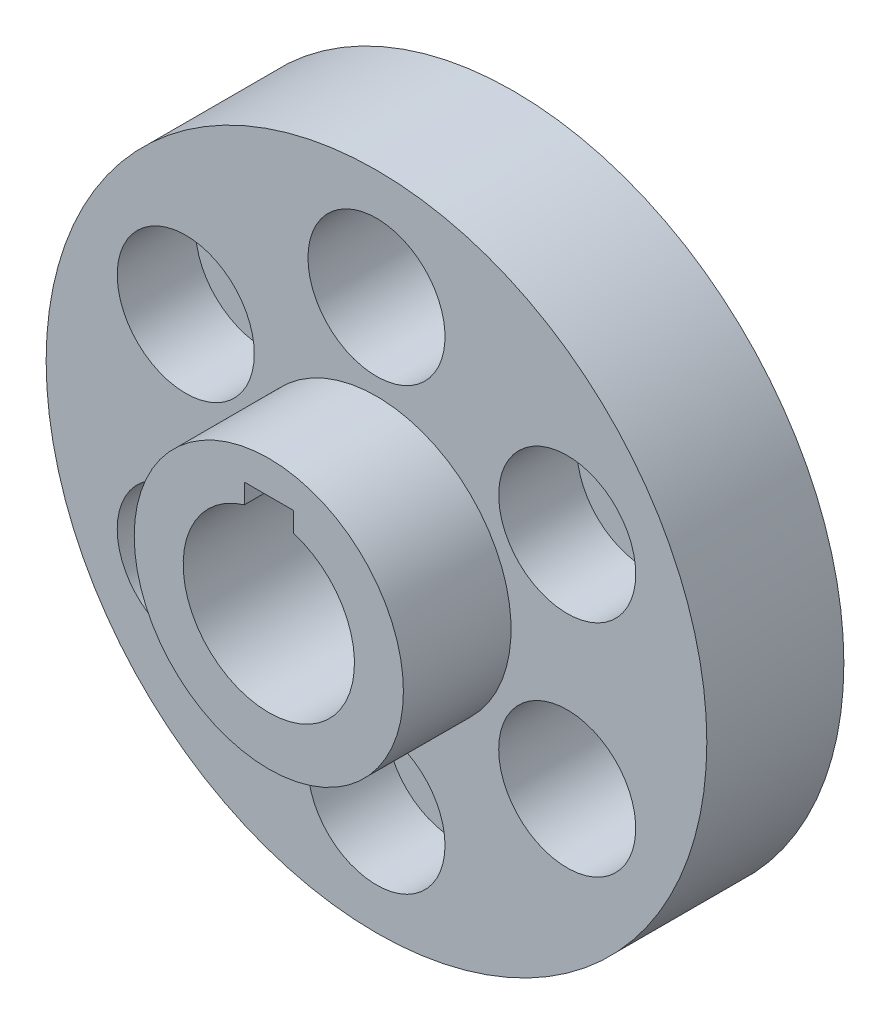
SolidWorks part; units mm, degrees
material "Cast Stainless Steel"
ref_plane "Front Plane" through (0, 0, 0) normal (0, 0, 1) x (1, 0, 0)
ref_plane "Top Plane" through (0, 0, 0) normal (0, 1, 0) x (1, 0, 0)
ref_plane "Right Plane" through (0, 0, 0) normal (1, 0, 0) x (0, 0, -1)
sketch "Sketch1" plane through (0, 0, 0) normal (0, 0, 1) x (1, 0, 0)
  line L0 (-5, 20.8) -> (5, 20.8)
  line L1 (0, 0) -> (50000, 0) construction
  line L2 (0, 3.0675) -> (0, 50003.0675) construction
  line L3 (5, 20.8) -> (5, 16.7705)
  line L4 (-5, 20.8) -> (-5, 16.7705)
  arc A0 (-5, 16.7705) -> (5, 16.7705) centre (0, 0) ccw
  circle A1 centre (0, 0) radius 27.5
  point P11 (0, 20.8)
  dimension "D1" = 35
  dimension "D2" = 55
  dimension "D3" = 20.8
  dimension "D4" = 10
extrude "Boss-Extrude1" add sketch "Sketch1" along normal blind 50
sketch "Sketch2" plane through (0, 0, 0) normal (0, 0, -1) x (-1, 0, 0)
  line L0 (0, 0) -> (-50000, 0) construction
  line L1 (0, 0) -> (0, 50000) construction
  circle A0 centre (0, 0) radius 67.5
  circle A1 centre (0, 45) radius 14
  circle A2 centre (38.9711, -22.5) radius 14
  circle A3 centre (-38.9711, -22.5) radius 14
  point P16 (0, 0)
  dimension "D1" = 135
  dimension "D2" = 28
  dimension "D3" = 45
extrude "Boss-Extrude2" add sketch "Sketch2" against normal blind 28
sketch "Sketch3" plane through (0, 0, 0) normal (0, 0, -1) x (-1, 0, 0)
  line L0 (0, 0) -> (-50000, 0) construction
  line L1 (0, 0) -> (0, 50000) construction
  circle A0 centre (0, -45) radius 9
  circle A2 centre (-38.9711, 22.5) radius 9
  circle A3 centre (38.9711, 22.5) radius 9
  point P13 (0, 0)
  dimension "D1" = 18
  dimension "D2" = 45
extrude "Cut-Extrude1" cut sketch "Sketch3" against normal blind 12 draft 7.5
sketch "Sketch4" plane through (0, 0, 28) normal (0, 0, 1) x (1, 0, 0)
  line L0 (0, 0) -> (0, -50000) construction
  line L1 (0, 0) -> (-50000, 0) construction
  circle A0 centre (0, -45) radius 14
  circle A1 centre (-38.9711, 22.5) radius 14
  circle A2 centre (38.9711, 22.5) radius 14
  point P13 (0, 0)
  dimension "D3" = 3
extrude "Cut-Extrude2" cut sketch "Sketch4" against normal blind 16
sketch "Sketch7" plane through (0, 0, 28) normal (0, 0, 1) x (1, 0, 0)
  line L0 (-5, 16.7705) -> (-5, 20.8)
  line L1 (-5, 20.8) -> (5, 20.8)
  line L2 (5, 20.8) -> (5, 16.7705)
  arc A0 (-5, 16.7705) -> (5, 16.7705) centre (0, 0) ccw
extrude "Cut-Extrude3" cut sketch "Sketch7" against normal blind 50
